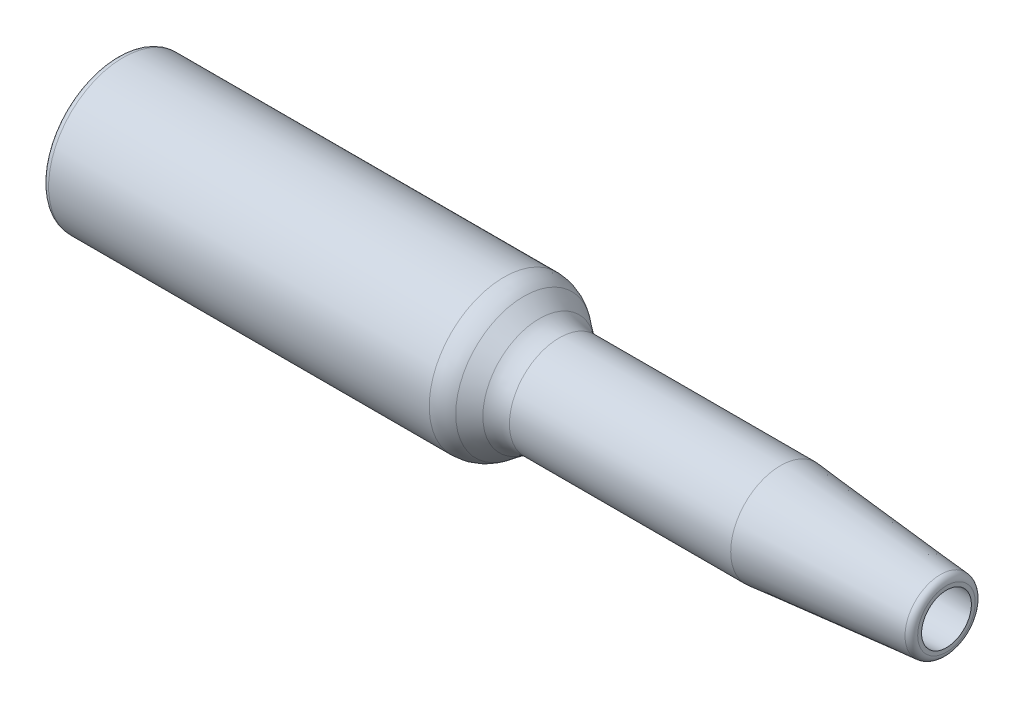
SolidWorks part; units mm, degrees
ref_plane "Спереди" through (0, 0, 0) normal (0, 0, 1) x (1, 0, 0)
ref_plane "Сверху" through (0, 0, 0) normal (0, 1, 0) x (1, 0, 0)
ref_plane "Справа" through (0, 0, 0) normal (1, 0, 0) x (0, 0, -1)
sketch "Эскиз1" plane through (0, 0, 0) normal (0, 0, 1) x (1, 0, 0)
  line L0 (-52.4417, 0) -> (71.8003, 0) construction
  line L1 (-22.3925, 1.835) -> (-22.3925, 2.25)
  line L2 (-22.3925, 2.25) -> (-10.3925, 2.25)
  line L3 (-10.3925, 2.25) -> (-9.3925, 1.5)
  line L4 (-9.3925, 1.5) -> (-2.3925, 1.5)
  line L5 (-2.3925, 1.5) -> (2.6075, 1.05)
  line L6 (2.6075, 1.05) -> (2.6075, 0.75)
  line L8 (-22.3925, 1.835) -> (-10.6027, 1.835)
  line L9 (-10.6027, 1.835) -> (-9.3925, 1.1)
  line L10 (-9.3925, 1.1) -> (-2.6633, 1.1)
  line L12 (-2.6633, 1.1) -> (2.6075, 0.75)
  dimension "D1" = 12
  dimension "D2" = 1
  dimension "D3" = 7
  dimension "D4" = 5
  dimension "D5" = 1.5
  dimension "D6" = 1.5
  dimension "D7" = 4.5
  dimension "D8" = 0.3
revolve "Повернуть1" add sketch "Эскиз1" angle 360 about L0
fillet "Скругление4" radius 0.2
fillet "Скругление5" radius 1
